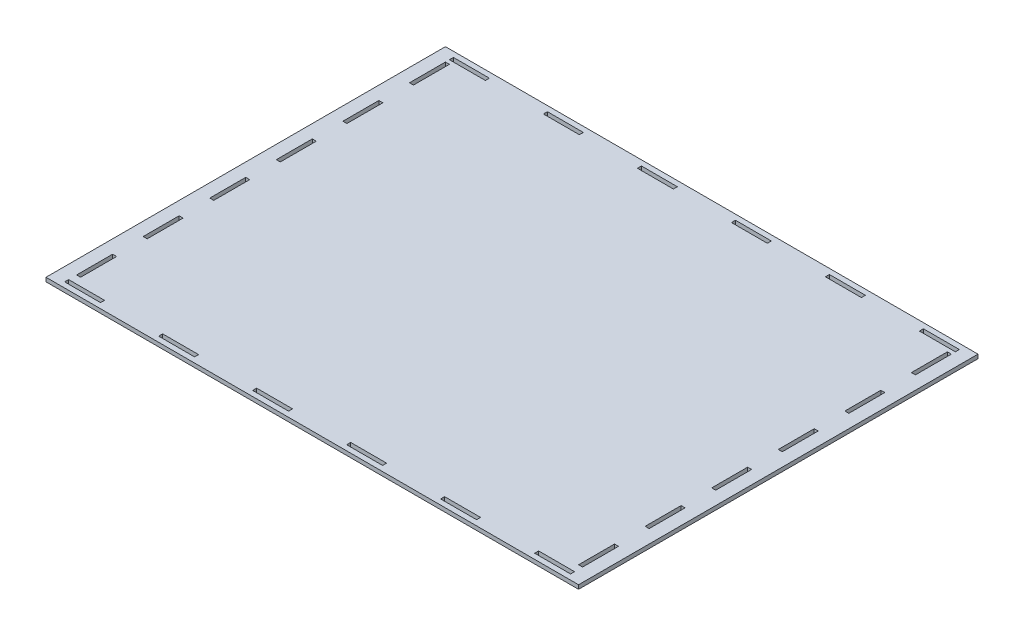
SolidWorks part; units mm, degrees
ref_plane "Plan de face" through (0, 0, 0) normal (0, 0, 1) x (1, 0, 0)
ref_plane "Plan de dessus" through (0, 0, 0) normal (0, 1, 0) x (1, 0, 0)
ref_plane "Plan de droite" through (0, 0, 0) normal (1, 0, 0) x (0, 0, -1)
sketch "Sketch1" plane through (0, 0, 0) normal (0, 1, 0) x (1, 0, 0)
  line L1 (-200, -150) -> (200, -150)
  line L2 (-200, -150) -> (-200, 150)
  line L3 (-200, 150) -> (200, 150)
  line L4 (200, -150) -> (200, 150)
  line L5 (-200, -150) -> (200, 150) construction
  line L6 (-200, 150) -> (200, -150) construction
  line L11 (50, -37.5) -> (-50, 37.5) construction
  line L12 (50, 37.5) -> (-50, -37.5) construction
  point P0 (0, 0)
  point P6 (0, 0)
  dimension "D1" = 400
  dimension "D2" = 300
  dimension "D3" = 100
  dimension "D4" = 75
extrude "Boss-Extrude2" add sketch "Sketch1" along normal blind 3
sketch "Sketch5" plane through (0, 3, 0) normal (0, 1, 0) x (1, 0, 0)
  line L0 (-200, 150) -> (-200, -150) construction
  line L1 (-190, 140) -> (-187, 140)
  line L2 (-190, 140) -> (-190, 113)
  line L3 (-190, 113) -> (-187, 113)
  line L4 (-187, 140) -> (-187, 113)
  line L5 (200, 150) -> (-200, 150) construction
  line L6 (-190, 90) -> (-190, 63)
  line L7 (-190, 90) -> (-187, 90)
  line L8 (-187, 90) -> (-187, 63)
  line L9 (-190, 63) -> (-187, 63)
  line L10 (-190, 40) -> (-190, 13)
  line L11 (-190, 40) -> (-187, 40)
  line L12 (-187, 40) -> (-187, 13)
  line L13 (-190, 13) -> (-187, 13)
  line L14 (-190, -10) -> (-190, -37)
  line L15 (-190, -10) -> (-187, -10)
  line L16 (-187, -10) -> (-187, -37)
  line L17 (-190, -37) -> (-187, -37)
  line L18 (-190, -60) -> (-190, -87)
  line L19 (-190, -60) -> (-187, -60)
  line L20 (-187, -60) -> (-187, -87)
  line L21 (-190, -87) -> (-187, -87)
  line L22 (-190, -110) -> (-190, -137)
  line L23 (-190, -110) -> (-187, -110)
  line L24 (-187, -110) -> (-187, -137)
  line L25 (-190, -137) -> (-187, -137)
  dimension "D1" = 3
  dimension "D2" = 27
  dimension "D3" = 10
  dimension "D4" = 10
  dimension "D5" = 6
extrude "Cut-Extrude4" cut sketch "Sketch5" against normal blind 3
sketch "Sketch6" plane through (0, 3, 0) normal (0, 1, 0) x (1, 0, 0)
  line L0 (200, -150) -> (200, 150) construction
  line L1 (187, 140) -> (190, 140)
  line L2 (187, 140) -> (187, 113)
  line L3 (187, 113) -> (190, 113)
  line L4 (190, 140) -> (190, 113)
  line L5 (200, 150) -> (-200, 150) construction
  line L6 (187, 90) -> (187, 63)
  line L7 (187, 90) -> (190, 90)
  line L8 (190, 90) -> (190, 63)
  line L9 (187, 63) -> (190, 63)
  line L10 (187, 40) -> (187, 13)
  line L11 (187, 40) -> (190, 40)
  line L12 (190, 40) -> (190, 13)
  line L13 (187, 13) -> (190, 13)
  line L14 (187, -10) -> (187, -37)
  line L15 (187, -10) -> (190, -10)
  line L16 (190, -10) -> (190, -37)
  line L17 (187, -37) -> (190, -37)
  line L18 (187, -60) -> (187, -87)
  line L19 (187, -60) -> (190, -60)
  line L20 (190, -60) -> (190, -87)
  line L21 (187, -87) -> (190, -87)
  line L22 (187, -110) -> (187, -137)
  line L23 (187, -110) -> (190, -110)
  line L24 (190, -110) -> (190, -137)
  line L25 (187, -137) -> (190, -137)
  dimension "D1" = 3
  dimension "D2" = 27
  dimension "D3" = 10
  dimension "D4" = 10
  dimension "D5" = 6
extrude "Cut-Extrude5" cut sketch "Sketch6" against normal blind 3
sketch "Sketch12" plane through (0, 0, 0) normal (0, -1, 0) x (1, 0, 0)
  line L0 (200, -150) -> (-200, -150) construction
  line L1 (-190, -143) -> (-163, -143)
  line L2 (-190, -143) -> (-190, -146)
  line L3 (-190, -146) -> (-163, -146)
  line L4 (-163, -143) -> (-163, -146)
  line L5 (-200, -150) -> (-200, 150) construction
  line L6 (-119.4, -143) -> (-119.4, -146)
  line L7 (-119.4, -143) -> (-92.4, -143)
  line L8 (-92.4, -143) -> (-92.4, -146)
  line L9 (-119.4, -146) -> (-92.4, -146)
  line L10 (-48.8, -143) -> (-48.8, -146)
  line L11 (-48.8, -143) -> (-21.8, -143)
  line L12 (-21.8, -143) -> (-21.8, -146)
  line L13 (-48.8, -146) -> (-21.8, -146)
  line L14 (21.8, -143) -> (21.8, -146)
  line L15 (21.8, -143) -> (48.8, -143)
  line L16 (48.8, -143) -> (48.8, -146)
  line L17 (21.8, -146) -> (48.8, -146)
  line L18 (92.4, -143) -> (92.4, -146)
  line L19 (92.4, -143) -> (119.4, -143)
  line L20 (119.4, -143) -> (119.4, -146)
  line L21 (92.4, -146) -> (119.4, -146)
  line L22 (163, -143) -> (163, -146)
  line L23 (163, -143) -> (190, -143)
  line L24 (190, -143) -> (190, -146)
  line L25 (163, -146) -> (190, -146)
  dimension "D1" = 27
  dimension "D2" = 3
  dimension "D3" = 4
  dimension "D4" = 10
  dimension "D5" = 4
  dimension "D6" = 6
extrude "Cut-Extrude10" cut sketch "Sketch12" against normal blind 10
sketch "Sketch13" plane through (0, 0, 0) normal (0, -1, 0) x (-1, 0, 0)
  line L1 (190, -146) -> (163, -146)
  line L2 (190, -146) -> (190, -143)
  line L3 (190, -143) -> (163, -143)
  line L4 (163, -146) -> (163, -143)
  line L5 (190, -110) -> (190, -137) construction
  line L6 (200, 150) -> (200, -150) construction
  line L7 (190, 143) -> (190, 146) construction
  line L8 (200, -150) -> (-200, -150) construction
  line L9 (119.4, -146) -> (119.4, -143)
  line L10 (119.4, -146) -> (92.4, -146)
  line L11 (92.4, -146) -> (92.4, -143)
  line L12 (119.4, -143) -> (92.4, -143)
  line L13 (48.8, -146) -> (48.8, -143)
  line L14 (48.8, -146) -> (21.8, -146)
  line L15 (21.8, -146) -> (21.8, -143)
  line L16 (48.8, -143) -> (21.8, -143)
  line L17 (-21.8, -146) -> (-21.8, -143)
  line L18 (-21.8, -146) -> (-48.8, -146)
  line L19 (-48.8, -146) -> (-48.8, -143)
  line L20 (-21.8, -143) -> (-48.8, -143)
  line L21 (-92.4, -146) -> (-92.4, -143)
  line L22 (-92.4, -146) -> (-119.4, -146)
  line L23 (-119.4, -146) -> (-119.4, -143)
  line L24 (-92.4, -143) -> (-119.4, -143)
  line L25 (-163, -146) -> (-163, -143)
  line L26 (-163, -146) -> (-190, -146)
  line L27 (-190, -146) -> (-190, -143)
  line L28 (-163, -143) -> (-190, -143)
  line L29 (190, -137) -> (187, -137) construction
  line L30 (-187, -137) -> (-190, -137) construction
  dimension "D1" = 27
  dimension "D2" = 3
  dimension "D3" = 0
  dimension "D4" = 10
  dimension "D5" = 10
  dimension "D6" = 4
  dimension "D8" = 9
  dimension "D9" = 9
  dimension "D7" = 6
extrude "Cut-Extrude11" cut sketch "Sketch13" against normal blind 10
